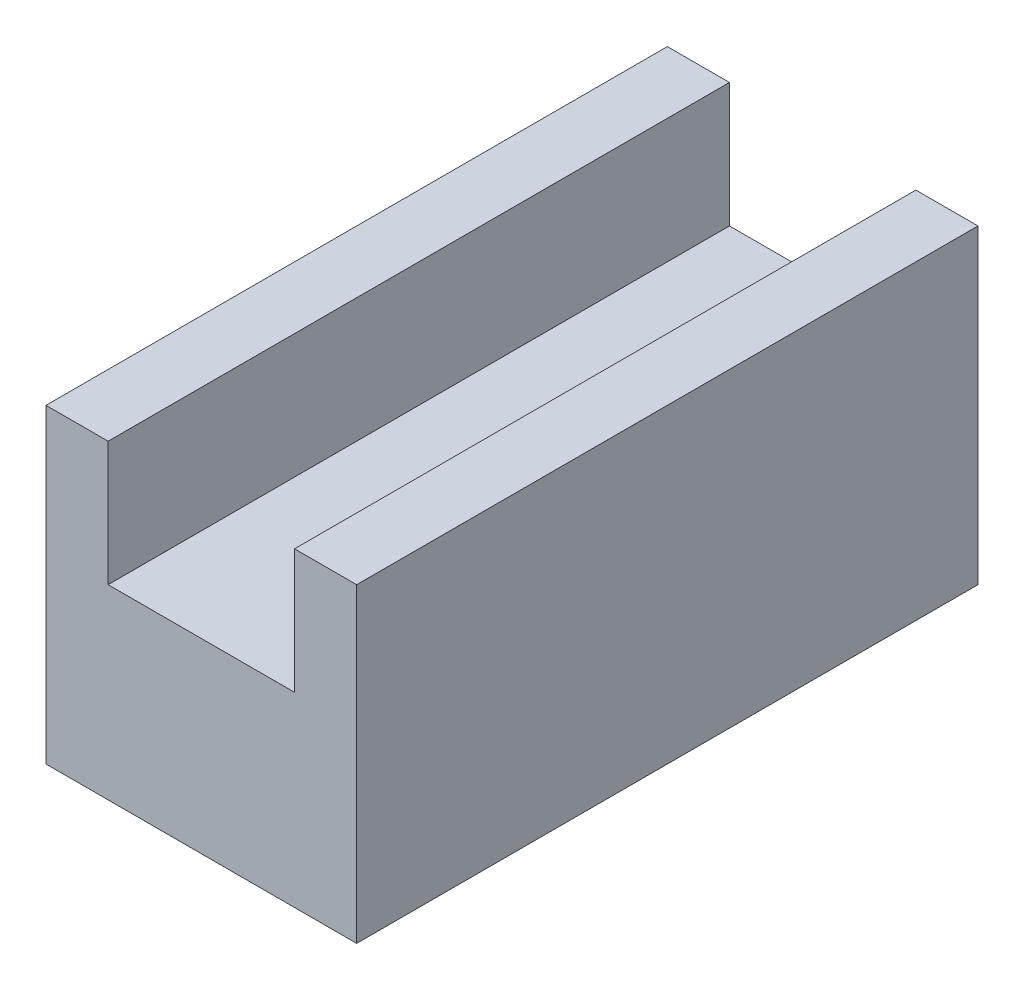
SolidWorks part; units mm, degrees
ref_plane "Front Plane" through (0, 0, 0) normal (0, 0, 1) x (1, 0, 0)
ref_plane "Top Plane" through (0, 0, 0) normal (0, 1, 0) x (1, 0, 0)
ref_plane "Right Plane" through (0, 0, 0) normal (1, 0, 0) x (0, 0, -1)
sketch "Sketch1" plane through (0, 0, 0) normal (0, 0, 1) x (1, 0, 0)
  line L1 (0, 0) -> (5, 0)
  line L2 (0, 0) -> (0, 5)
  line L3 (0, 5) -> (5, 5)
  line L4 (5, 0) -> (5, 5)
  dimension "D1" = 5
  dimension "D2" = 5
extrude "Boss-Extrude1" add sketch "Sketch1" along normal blind 10
sketch "Sketch2" plane through (0, 5, 0) normal (0, 1, 0) x (1, 0, 0)
  line L0 (5, 0) -> (0, 0) construction
  line L1 (1, 0) -> (4, 0)
  line L2 (1, 0) -> (1, -10)
  line L3 (1, -10) -> (4, -10)
  line L4 (4, 0) -> (4, -10)
  line L5 (5, -10) -> (0, -10) construction
  line L6 (0, -10) -> (0, 0) construction
  dimension "D1" = 3
  dimension "D2" = 1
extrude "Cut-Extrude1" cut sketch "Sketch2" against normal blind 2
